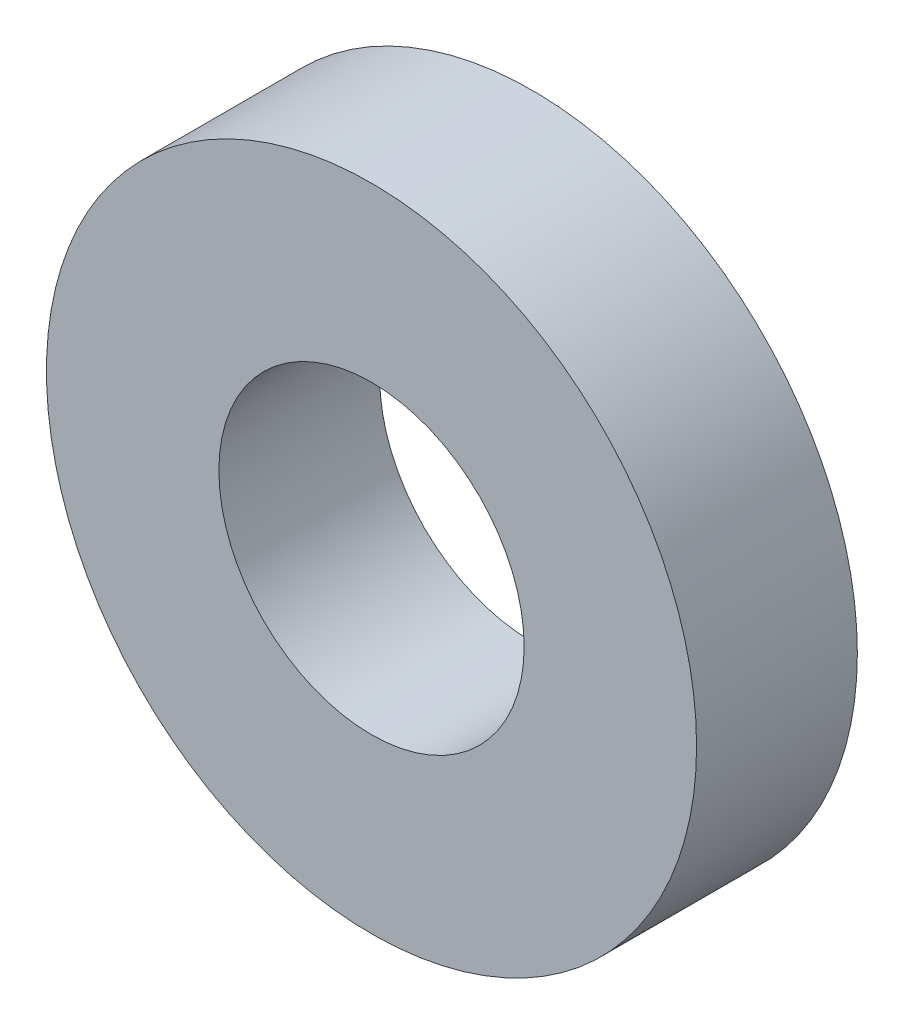
SolidWorks part; units mm, degrees
ref_plane "Front Plane" through (0, 0, 0) normal (0, 0, 1) x (1, 0, 0)
ref_plane "Top Plane" through (0, 0, 0) normal (0, 1, 0) x (1, 0, 0)
ref_plane "Right Plane" through (0, 0, 0) normal (1, 0, 0) x (0, 0, -1)
sketch "CurveSketch" plane through (0, 0, 0) normal (0, 0, 1) x (1, 0, 0)
  circle A0 centre (5.371, -7.193) radius 23.719
  circle A1 centre (5.371, -7.193) radius 11.137
  dimension "D1" = 23.719
  dimension "D2" = 11.137
extrude "CurveBoss" add sketch "CurveSketch" along normal blind 11.731
